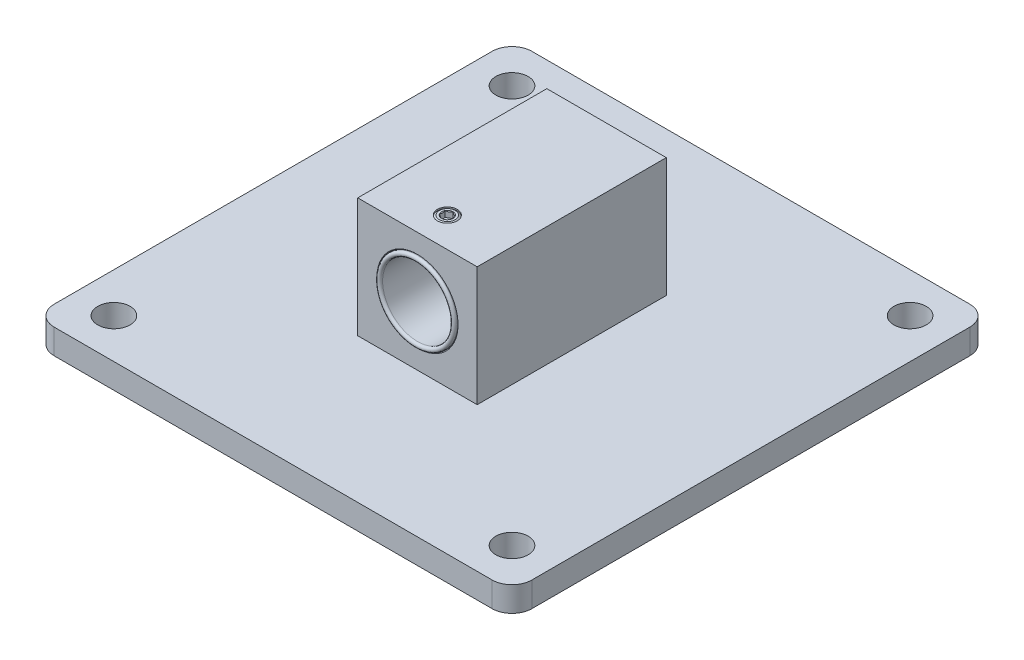
SolidWorks part; units mm, degrees
ref_plane "Front" through (0, 0, 0) normal (0, 0, 1) x (1, 0, 0)
ref_plane "Top" through (0, 0, 0) normal (0, 1, 0) x (1, 0, 0)
ref_plane "Right" through (0, 0, 0) normal (1, 0, 0) x (0, 0, -1)
sketch "Sketch1" plane through (0, 0, 0) normal (0, 1, 0) x (1, 0, 0)
  line L0 (-76.2, 63.5) -> (-63.5, 63.5) construction
  line L1 (-69.85, 76.2) -> (69.85, 76.2)
  line L2 (-76.2, 69.85) -> (-76.2, -69.85)
  line L3 (-69.85, -76.2) -> (69.85, -76.2)
  line L4 (76.2, 69.85) -> (76.2, -69.85)
  line L5 (-76.2, 76.2) -> (76.2, -76.2) construction
  line L6 (-76.2, -76.2) -> (76.2, 76.2) construction
  line L7 (-63.5, 63.5) -> (-63.5, 76.2) construction
  line L8 (0, 76.2) -> (0, 0) construction
  line L9 (0, 0) -> (-76.2, 0) construction
  arc A0 (69.85, 76.2) -> (76.2, 69.85) centre (69.85, 69.85) cw
  arc A1 (-69.85, 76.2) -> (-76.2, 69.85) centre (-69.85, 69.85) ccw
  arc A2 (-76.2, -69.85) -> (-69.85, -76.2) centre (-69.85, -69.85) ccw
  arc A3 (69.85, -76.2) -> (76.2, -69.85) centre (69.85, -69.85) ccw
  circle A4 centre (-63.5, 63.5) radius 5.1562
  circle A5 centre (63.5, 63.5) radius 5.1562
  circle A6 centre (63.5, -63.5) radius 5.1562
  circle A7 centre (-63.5, -63.5) radius 5.1562
  point P0 (0, 0)
  dimension "D1" = 6.35
  dimension "D4" = 10.3124
  dimension "D2" = 152.4
  dimension "D3" = 12.7
extrude "Boss-Extrude1" add sketch "Sketch1" along normal mid plane 7.9375
sketch "Sketch2" plane through (0, 0, 0) normal (0, 0, 1) x (1, 0, 0)
  line L0 (-19.05, 3.9688) -> (19.05, 3.9688)
  line L1 (-69.85, 3.9688) -> (69.85, 3.9688) construction
  line L2 (0, 0) -> (0, 3.9688) construction
  line L3 (-19.05, 3.9688) -> (-19.05, 42.0688)
  line L4 (-19.05, 42.0688) -> (19.05, 42.0688)
  line L5 (19.05, 42.0688) -> (19.05, 3.9688)
  line L6 (0, 42.0688) -> (0, 3.9688) construction
  circle A0 centre (0, 23.0188) radius 12.7
  dimension "D2" = 25.4
  dimension "D1" = 38.1
extrude "Boss-Extrude2" add sketch "Sketch2" along normal mid plane 60.325
chamfer "Chamfer1" distance 0.254 angle 45 2 edges at (12.7, 23.0188, -30.1625) (12.7, 23.0188, 30.1625)
sketch "Sketch3" plane through (0, 0, 0) normal (1, 0, 0) x (0, 0, -1)
  line L0 (-30.1625, 35.7188) -> (0, 35.7188)
  line L1 (-30.1625, 35.9728) -> (-30.1625, 10.0647) construction
  line L2 (-30.1625, 23.0188) -> (30.1625, 23.0188) construction
  line L3 (30.1625, 10.0648) -> (30.1625, 35.9727) construction
  line L4 (-30.1625, 34.1312) -> (0, 34.1312)
  line L5 (0, 35.7188) -> (0, 34.1312)
  line L6 (11.9062, 35.7188) -> (29.3687, 35.7187)
  line L7 (11.9062, 35.7188) -> (11.9062, 34.1312)
  line L8 (11.9062, 34.1312) -> (29.3687, 34.1313)
  arc A0 (-30.1625, 35.7188) -> (-30.1625, 34.1312) centre (-30.1625, 34.925) ccw
  arc A1 (29.3687, 34.1313) -> (29.3687, 35.7187) centre (29.3687, 34.925) ccw
  dimension "D1" = 1.5875
  dimension "D2" = 25.4
  dimension "D3" = 30.1625
  dimension "D4" = 17.4625
revolve "Revolve1" add sketch "Sketch3" angle 360 mid plane about L2
sketch "Sketch4" plane through (0, 42.0688, 0) normal (0, 1, 0) x (1, 0, 0)
  line L0 (0, -30.1625) -> (0, -20.6375) construction
  line L1 (19.05, -30.1625) -> (-19.05, -30.1625) construction
  circle A0 centre (0, -20.6375) radius 3.175
  dimension "D2" = 6.35
  dimension "D1" = 9.525
extrude "Cut-Extrude1" cut sketch "Sketch4" against normal up to next
sketch "Sketch5" plane through (0, 0, 0) normal (1, 0, 0) x (0, 0, -1)
  line L0 (-23.1775, 42.0688) -> (-22.4701, 42.0688)
  line L1 (-17.4625, 42.0688) -> (-23.8125, 42.0688) construction
  line L2 (-30.1625, 42.0688) -> (30.1625, 42.0688) construction
  line L3 (-20.6375, 42.0688) -> (-20.6375, 40.1638) construction
  line L4 (-23.1775, 42.0688) -> (-23.8125, 41.6241)
  line L5 (-23.8125, 41.6241) -> (-23.8125, 37.1539)
  line L6 (-23.8125, 37.1539) -> (-22.3774, 35.7188)
  line L7 (-22.3774, 35.7188) -> (-20.6375, 35.7188)
  line L8 (-20.6375, 35.7188) -> (-20.6375, 40.1638)
  line L9 (-20.6375, 40.1638) -> (-22.225, 40.1638)
  line L10 (-22.225, 40.1638) -> (-22.225, 41.8236)
  line L11 (-22.4701, 42.0688) -> (-22.225, 41.8236)
  line L12 (-23.8125, 35.7188) -> (-17.4625, 35.7188) construction
  spline S0 degree 2 poles (-17.4625, 35.7188) (-20.6375, 34.925) (-23.8125, 35.7188) knots 0 0 0 1 1 1 weights 0.009525 0.0127 0.015875 construction
  dimension "D1" = 6.35
  dimension "D2" = 35
  dimension "D3" = 5.08
  dimension "D4" = 3.6652
  dimension "D5" = 3.175
  dimension "D6" = 45
  dimension "D7" = 1.905
  dimension "D8" = 45
  dimension "D9" = 3.4798
revolve "Revolve2" add sketch "Sketch5" angle 360 mid plane about L3
sketch "Sketch6" plane through (0, 42.0688, 0) normal (0, 1, 0) x (1, 0, 0)
  line L0 (0, -20.6375) -> (0, -18.8044) construction
  line L1 (0, -18.8044) -> (-1.5875, -19.721)
  line L2 (-1.5875, -19.721) -> (-1.5875, -21.554)
  line L3 (-1.5875, -21.554) -> (0, -22.4706)
  line L4 (0, -22.4706) -> (1.5875, -21.554)
  line L5 (1.5875, -21.554) -> (1.5875, -19.721)
  line L6 (1.5875, -19.721) -> (0, -18.8044)
  circle A0 centre (0, -20.6375) radius 1.5875 construction
  circle A2 centre (0, -20.6375) radius 1.5875 construction
extrude "Cut-Extrude2" cut sketch "Sketch6" against normal up to surface (1.905 mm away) up to face at (0, 40.1638, 22.225)
